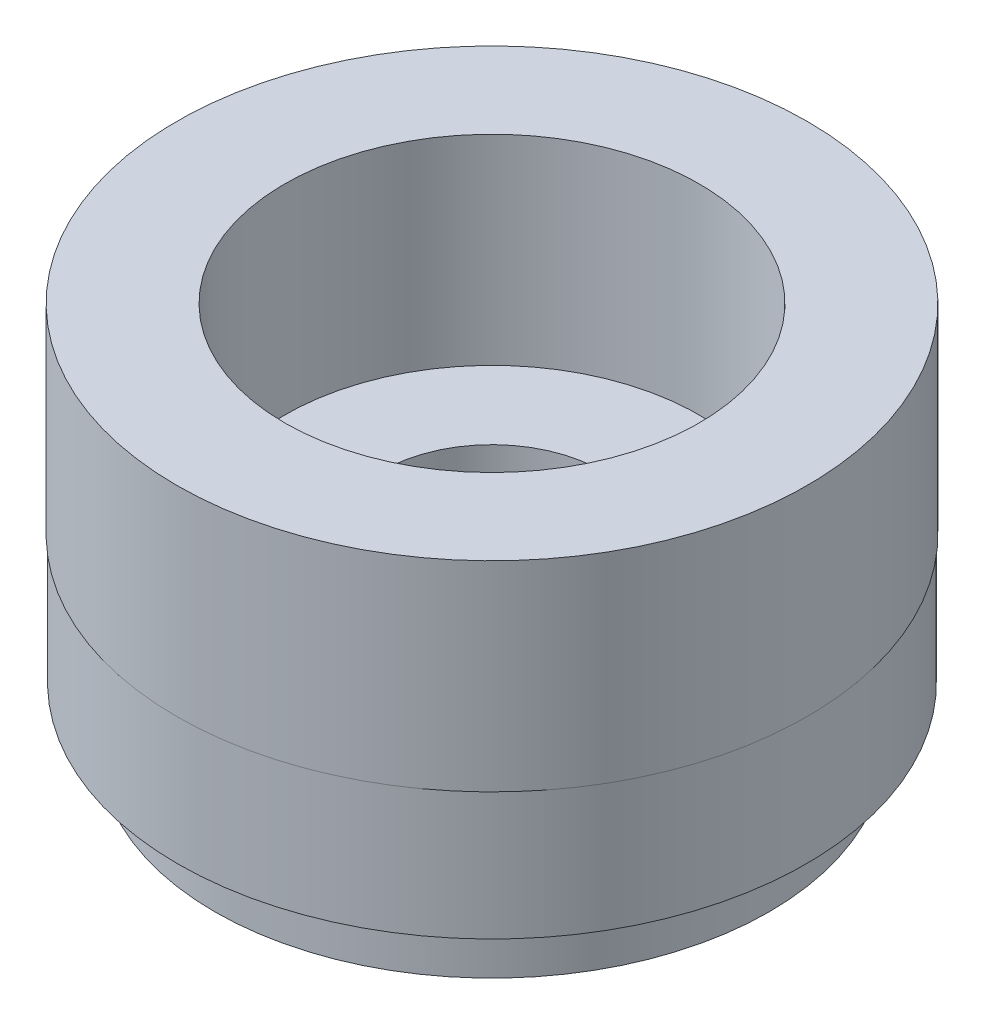
SolidWorks part; units mm, degrees
ref_plane "Front Plane" through (0, 0, 0) normal (0, 0, 1) x (1, 0, 0)
ref_plane "Top Plane" through (0, 0, 0) normal (0, 1, 0) x (1, 0, 0)
ref_plane "Right Plane" through (0, 0, 0) normal (1, 0, 0) x (0, 0, -1)
sketch "Sketch1" plane through (0, 0, 0) normal (0, 1, 0) x (1, 0, 0)
  circle A0 centre (0, 0) radius 3.9878
  dimension "D1" = 7.9756
extrude "Boss-Extrude1" add sketch "Sketch1" along normal blind 1.6256
sketch "Sketch2" plane through (0, 1.6256, 0) normal (0, 1, 0) x (1, 0, 0)
  circle A0 centre (0, 0) radius 4.0005
  dimension "D1" = 8.001
extrude "Boss-Extrude2" add sketch "Sketch2" along normal blind 2.54
sketch "Sketch3" plane through (0, 0, 0) normal (0, -1, 0) x (1, 0, 0)
  circle A0 centre (0, 0) radius 3.5179
  dimension "D1" = 7.0358
extrude "Boss-Extrude3" add sketch "Sketch3" along normal blind 0.762
sketch "Sketch4" plane through (0, -0.762, 0) normal (0, -1, 0) x (1, 0, 0)
  circle A0 centre (0, 0) radius 3.0099
  dimension "D1" = 6.0198
extrude "Cut-Extrude1" cut sketch "Sketch4" against normal up to surface (0.762 mm away) up to face at (0, 0, -3.5179)
sketch "Sketch5" plane through (0, 4.1656, 0) normal (0, 1, 0) x (1, 0, 0)
  circle A0 centre (0, 0) radius 2.6289
  dimension "D1" = 5.2578
extrude "Cut-Extrude2" cut sketch "Sketch5" against normal blind 2.54
sketch "Sketch6" plane through (0, 1.6256, 0) normal (0, 1, 0) x (1, 0, 0)
  circle A0 centre (0, 0) radius 1.397
  dimension "D1" = 2.794
extrude "Cut-Extrude3" cut sketch "Sketch6" against normal through all
